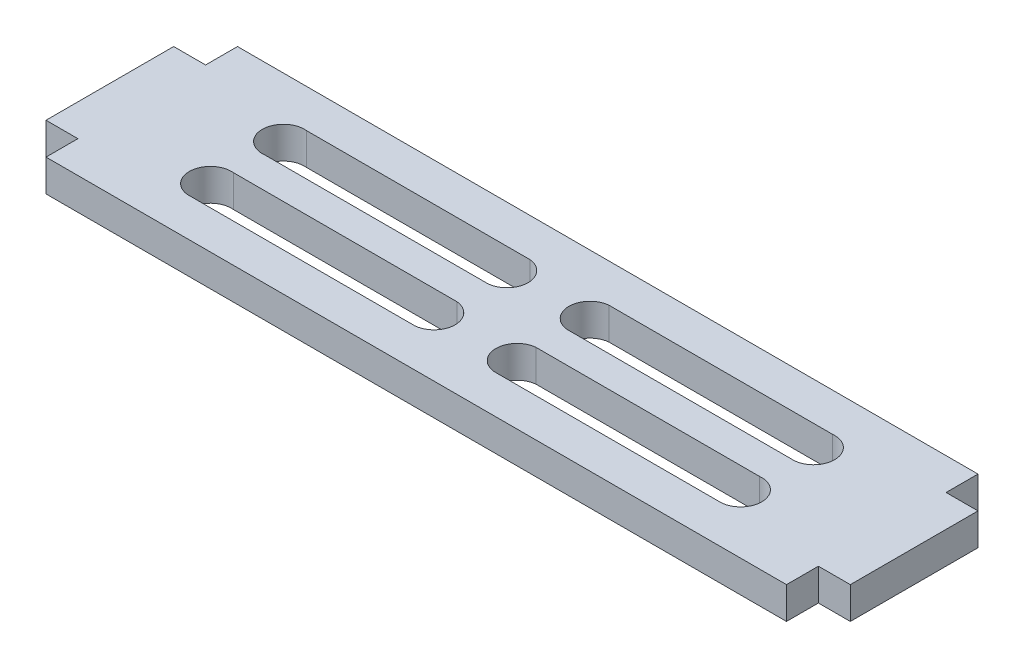
SolidWorks part; units mm, degrees
ref_plane "Front Plane" through (0, 0, 0) normal (0, 0, 1) x (1, 0, 0)
ref_plane "Top Plane" through (0, 0, 0) normal (0, 1, 0) x (1, 0, 0)
ref_plane "Right Plane" through (0, 0, 0) normal (1, 0, 0) x (0, 0, -1)
sketch "Sketch2" plane through (0, 0, 0) normal (0, 1, 0) x (1, 0, 0)
  line L0 (46.5893, 13.309) -> (51.5893, 13.309)
  line L1 (27.5893, 13.309) -> (46.5893, 13.309)
  line L3 (-20.9107, -16.691) -> (95.0893, -16.691)
  line L4 (95.0893, 13.309) -> (95.0893, 8.309)
  line L5 (95.0893, 8.309) -> (100.0893, 8.309)
  line L7 (95.0893, -11.691) -> (100.0893, -11.691)
  line L8 (100.0893, 8.309) -> (100.0893, -11.691)
  line L13 (95.0893, -11.691) -> (95.0893, -16.691)
  line L18 (51.5893, 13.309) -> (95.0893, 13.309)
  line L19 (37.0893, -16.691) -> (37.0893, 34.6569) construction
  line L26 (78.2715, -10.691) -> (43.2715, -10.691)
  line L27 (78.2715, -4.1219) -> (43.2715, -4.1219)
  line L28 (100.0893, -1.691) -> (-25.9107, -1.691) construction
  line L35 (22.5893, 13.309) -> (-20.9107, 13.309)
  line L36 (-20.9107, -11.691) -> (-20.9107, -16.691)
  line L37 (-25.9107, 8.309) -> (-25.9107, -11.691)
  line L38 (-20.9107, -11.691) -> (-25.9107, -11.691)
  line L39 (-20.9107, 8.309) -> (-25.9107, 8.309)
  line L40 (-20.9107, 13.309) -> (-20.9107, 8.309)
  line L41 (27.5893, 13.309) -> (22.5893, 13.309)
  line L42 (-4.0929, -4.1219) -> (30.9071, -4.1219)
  line L43 (-4.0929, -10.691) -> (30.9071, -10.691)
  line L44 (-4.0929, 7.309) -> (30.9071, 7.309)
  line L45 (-4.0929, 0.7398) -> (30.9071, 0.7398)
  line L46 (78.2715, 0.7398) -> (43.2715, 0.7398)
  line L47 (78.2715, 7.309) -> (43.2715, 7.309)
  arc A4 (43.2715, -4.1219) -> (43.2715, -10.691) centre (43.5901, -7.4064) ccw
  arc A5 (78.2715, -4.1219) -> (78.2715, -10.691) centre (78.6173, -7.4064) cw
  arc A6 (-4.0929, -4.1219) -> (-4.0929, -10.691) centre (-4.4387, -7.4064) ccw
  arc A7 (30.9071, -4.1219) -> (30.9071, -10.691) centre (30.5885, -7.4064) cw
  arc A8 (30.9071, 0.7398) -> (30.9071, 7.309) centre (30.5885, 4.0244) ccw
  arc A9 (-4.0929, 0.7398) -> (-4.0929, 7.309) centre (-4.4387, 4.0244) cw
  arc A10 (78.2715, 0.7398) -> (78.2715, 7.309) centre (78.6173, 4.0244) ccw
  arc A11 (43.2715, 0.7398) -> (43.2715, 7.309) centre (43.5901, 4.0244) cw
  point P18 (37.0893, -1.691)
  point P46 (37.0893, 13.309)
  dimension "D1" = 6
  dimension "D2" = 30
  dimension "D3" = 5
  dimension "D4" = 20
  dimension "D5" = 5
  dimension "D6" = 116
extrude "Boss-Extrude1" add sketch "Sketch2" along normal blind 5
